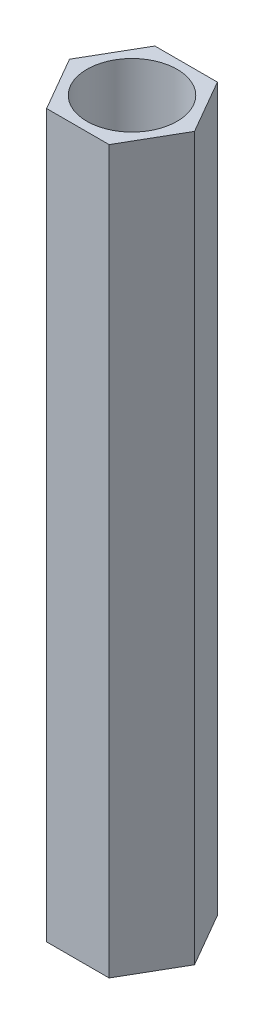
SolidWorks part; units mm, degrees
material "Copper"
ref_plane "Front Plane" through (0, 0, 0) normal (0, 0, 1) x (1, 0, 0)
ref_plane "Top Plane" through (0, 0, 0) normal (0, 1, 0) x (1, 0, 0)
ref_plane "Right Plane" through (0, 0, 0) normal (1, 0, 0) x (0, 0, -1)
sketch "Sketch1" plane through (0, 0, 0) normal (0, 1, 0) x (1, 0, 0)
  line L1 (1.7321, 3) -> (-1.7321, 3)
  line L2 (-1.7321, 3) -> (-3.4641, 0)
  line L3 (-3.4641, 0) -> (-1.7321, -3)
  line L4 (-1.7321, -3) -> (1.7321, -3)
  line L5 (1.7321, -3) -> (3.4641, 0)
  line L6 (3.4641, 0) -> (1.7321, 3)
  circle A0 centre (0, 0) radius 3 construction
  circle A1 centre (0, 0) radius 2.5
  dimension "D1" = 6
  dimension "D2" = 5
extrude "Boss-Extrude1" add sketch "Sketch1" along normal mid plane 40
